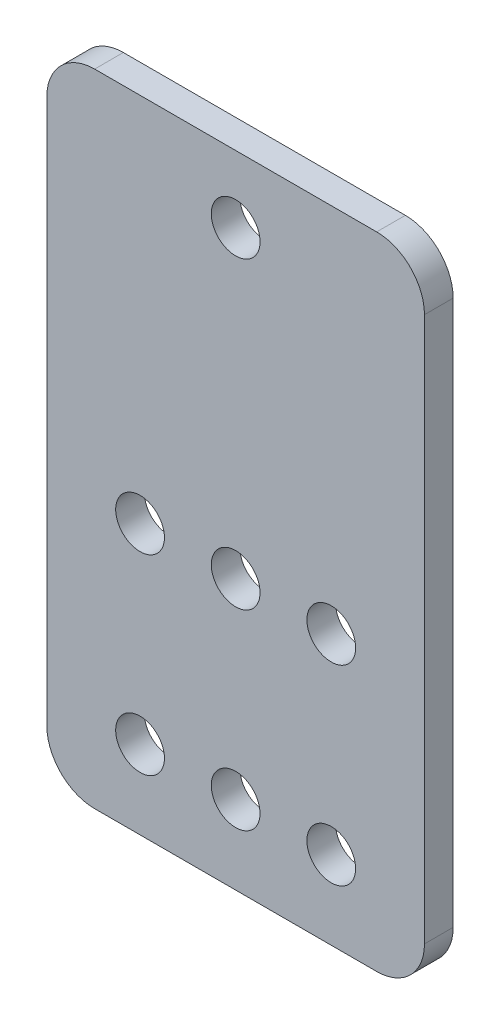
SolidWorks part; units mm, degrees
ref_plane "Front Plane" through (0, 0, 0) normal (0, 0, 1) x (1, 0, 0)
ref_plane "Top Plane" through (0, 0, 0) normal (0, 1, 0) x (1, 0, 0)
ref_plane "Right Plane" through (0, 0, 0) normal (1, 0, 0) x (0, 0, -1)
sketch "Sketch1" plane through (0, 0, 0) normal (0, 0, 1) x (1, 0, 0)
  line L0 (-23.2741, -25.29) -> (28.6211, -25.29) construction
  line L1 (-14.75, -33.5) -> (14.75, -33.5)
  line L2 (-19.75, -28.5) -> (-19.75, 28.5)
  line L3 (-14.75, 33.5) -> (14.75, 33.5)
  line L4 (19.75, -28.5) -> (19.75, 28.5)
  line L5 (0, 33.5) -> (0, -33.5) construction
  line L6 (-19.75, 0) -> (19.75, 0) construction
  line L7 (-24.9139, -5.29) -> (29.6821, -5.29) construction
  line L8 (-10, -39.8148) -> (-10, 20.0102) construction
  line L9 (0, -37.5183) -> (0, 19.0916) construction
  line L10 (10, -39.011) -> (10, 17.484) construction
  line L11 (-28.5515, 26.5) -> (34.259, 26.5) construction
  arc A0 (14.75, 33.5) -> (19.75, 28.5) centre (14.75, 28.5) cw
  arc A1 (14.75, -33.5) -> (19.75, -28.5) centre (14.75, -28.5) ccw
  arc A2 (-14.75, -33.5) -> (-19.75, -28.5) centre (-14.75, -28.5) cw
  arc A3 (-19.75, 28.5) -> (-14.75, 33.5) centre (-14.75, 28.5) cw
  circle A4 centre (-10, -5.29) radius 2.55
  circle A5 centre (0, -5.29) radius 2.55
  circle A6 centre (10, -5.29) radius 2.55
  circle A7 centre (-10, -25.29) radius 2.55
  circle A8 centre (0, -25.29) radius 2.55
  circle A9 centre (0, 26.5) radius 2.55
  circle A11 centre (10, -25.29) radius 2.55
  point P0 (0, 0)
  point P6 (19.75, 33.5)
  point P9 (19.75, -33.5)
  dimension "D3" = 5
  dimension "D10" = 5.1
  dimension "D1" = 67
  dimension "D2" = 39.5
  dimension "D4" = 8.21
  dimension "D5" = 28.21
  dimension "D6" = 9.75
  dimension "D7" = 19.75
  dimension "D8" = 29.75
  dimension "D9" = 60
extrude "Boss-Extrude1" add sketch "Sketch1" along normal blind 3
